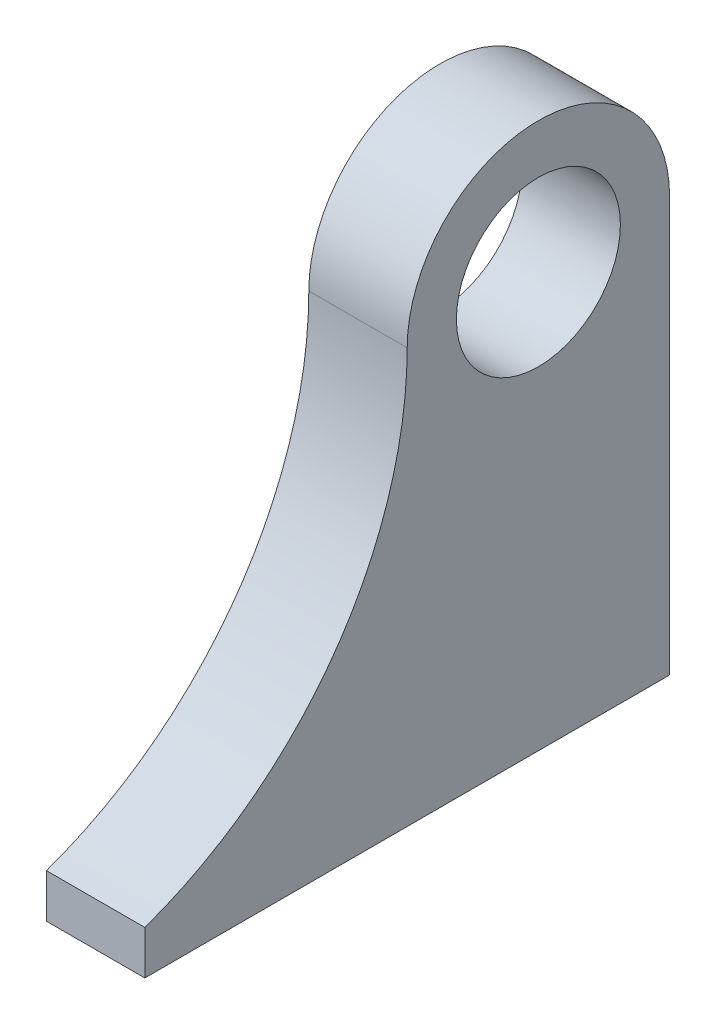
SolidWorks part; units mm, degrees
ref_plane "Alzado" through (0, 0, 0) normal (0, 0, 1) x (1, 0, 0)
ref_plane "Planta" through (0, 0, 0) normal (0, 1, 0) x (1, 0, 0)
ref_plane "Vista lateral" through (0, 0, 0) normal (1, 0, 0) x (0, 0, -1)
sketch "Croquis1" plane through (0, 0, 0) normal (0, 1, 0) x (1, 0, 0)
  line L0 (63.5, 63.5) -> (63.5, 390.652) construction
  line L1 (0, 0) -> (654.05, 0) construction
  line L2 (0, 0) -> (0, 454.152) construction
  line L3 (0, 454.152) -> (654.05, 454.152) construction
  line L4 (654.05, 0) -> (654.05, 454.152) construction
  line L5 (63.5, 390.652) -> (590.55, 390.652) construction
  line L6 (590.55, 63.5) -> (590.55, 390.652) construction
  line L7 (63.5, 63.5) -> (590.55, 63.5) construction
  line L8 (42.3333, 411.8187) -> (611.7167, 411.8187) construction
  line L9 (611.7167, 42.3333) -> (611.7167, 411.8187) construction
  line L10 (42.3333, 42.3333) -> (611.7167, 42.3333) construction
  line L11 (42.3333, 42.3333) -> (42.3333, 411.8187) construction
  line L12 (606.9542, 411.8187) -> (606.9542, 454.152) construction
  line L14 (606.9542, 454.152) -> (602.1917, 454.152)
  line L15 (606.9542, 454.152) -> (606.9542, 411.8187)
  line L16 (606.9542, 411.8187) -> (602.1917, 411.8187)
  line L17 (602.1917, 454.152) -> (602.1917, 411.8187)
  dimension "D1" = 654.05
  dimension "D2" = 454.152
  dimension "D3" = 42.3333
  dimension "D4" = 369.4853
  dimension "D5" = 63.5
  dimension "D6" = 569.3833
  dimension "D7" = 527.05
  dimension "D8" = 327.152
  dimension "D9" = 42.3333
  dimension "D10" = 4.7625
  dimension "D11" = 4.7625
  dimension "D12" = 42.3333
  dimension "D13" = 21.1667
extrude "Saliente-Extruir1" add sketch "Croquis1" along normal blind 26.416
sketch "Croquis2" plane through (606.9542, 0, 0) normal (1, 0, 0) x (0, 0, -1)
  line L0 (432.9853, 26.416) -> (432.9853, 0) construction
  line L1 (411.8187, 26.416) -> (454.152, 26.416) construction
  line L2 (411.8187, 0) -> (454.152, 0) construction
  line L3 (439.3353, 20.066) -> (439.3353, 0)
  line L4 (439.3353, 0) -> (413.9353, 0)
  line L5 (413.9353, 0) -> (411.8187, 0)
  line L6 (413.9353, 0) -> (411.8187, 0) construction
  line L7 (413.9353, 0) -> (413.9353, 2.12)
  line L8 (426.6353, 20.066) -> (432.9853, 20.066) construction
  line L9 (411.8187, 0) -> (411.8187, 26.416)
  line L10 (411.8187, 26.416) -> (454.152, 26.416)
  line L11 (454.152, 26.416) -> (454.152, 0)
  line L12 (454.152, 0) -> (439.3353, 0)
  circle A0 centre (432.9853, 20.066) radius 3.9688
  arc A1 (439.3353, 20.066) -> (426.6353, 20.066) centre (432.9853, 20.066) ccw
  arc A2 (413.9353, 2.12) -> (426.6353, 20.066) centre (407.6058, 20.066) ccw
  point P10 (432.9853, 20.066)
  line M4 (411.8187, 0) -> (454.152, 0)
  line M5 (454.152, 0) -> (454.152, 26.416)
  line M6 (454.152, 26.416) -> (411.8187, 26.416)
  line M7 (411.8187, 26.416) -> (411.8187, 0)
  dimension "D4" = 7.9375
  dimension "D5" = 2.12
  dimension "D3" = 6.35
  dimension "D1" = 25.4
  dimension "D2" = 2.1167
extrude "Cortar-Extruir1" cut sketch "Croquis2" against normal blind 25.4 contours L7 A2 A1 L10 M7 M4 | A1 L3 M4 M5 M6 | A0
